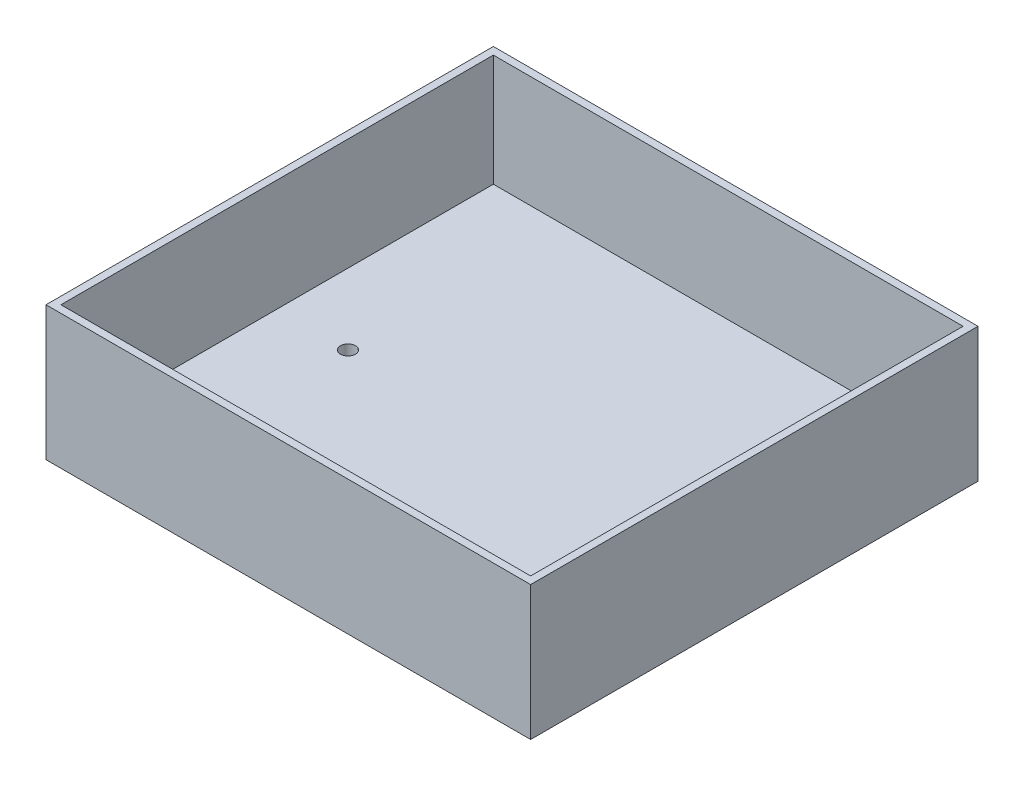
SolidWorks part; units mm, degrees
ref_plane "Front Plane" through (0, 0, 0) normal (0, 0, 1) x (1, 0, 0)
ref_plane "Top Plane" through (0, 0, 0) normal (0, 1, 0) x (1, 0, 0)
ref_plane "Right Plane" through (0, 0, 0) normal (1, 0, 0) x (0, 0, -1)
sketch "Sketch1" plane through (0, 0, 0) normal (0, 1, 0) x (1, 0, 0)
  line L1 (32.5, 30) -> (-32.5, 30)
  line L2 (32.5, 30) -> (32.5, -30)
  line L3 (32.5, -30) -> (-32.5, -30)
  line L4 (-32.5, 30) -> (-32.5, -30)
  line L5 (32.5, 30) -> (-32.5, -30) construction
  line L6 (32.5, -30) -> (-32.5, 30) construction
  point P0 (0, 0)
  dimension "D1" = 60
  dimension "D2" = 65
extrude "Boss-Extrude1" add sketch "Sketch1" along normal blind 18
shell "Shell1" thickness 3
hole_wizard "Ø2.0mm Dowel Hole1" positions "Sketch3" profile "Sketch4" hole size "Ø2.0" standard "ANSI Metric" end condition through all
sketch "Sketch3" plane through (0, 3, 0) normal (0, 1, 0) x (1, 0, 0)
  line L0 (-22, 0) -> (22, 0) construction
  point P2 (-22, 0)
  point P3 (22, 0)
  dimension "D1" = 44
sketch "Sketch4" plane through (-22, 3, 0) normal (1, 0, 0) x (0, 0, 1)
  line L0 (0, 0) -> (0, 3)
  line L1 (0, 3) -> (1, 3)
  line L2 (1, 3) -> (1, 0)
  line L5 (1, 0) -> (0, 0)
  line L11 (0, -6.35) -> (0, 107.95) construction
  dimension "Thru Hole Dia." = 2
  dimension "Thru Hole Depth" = 3
